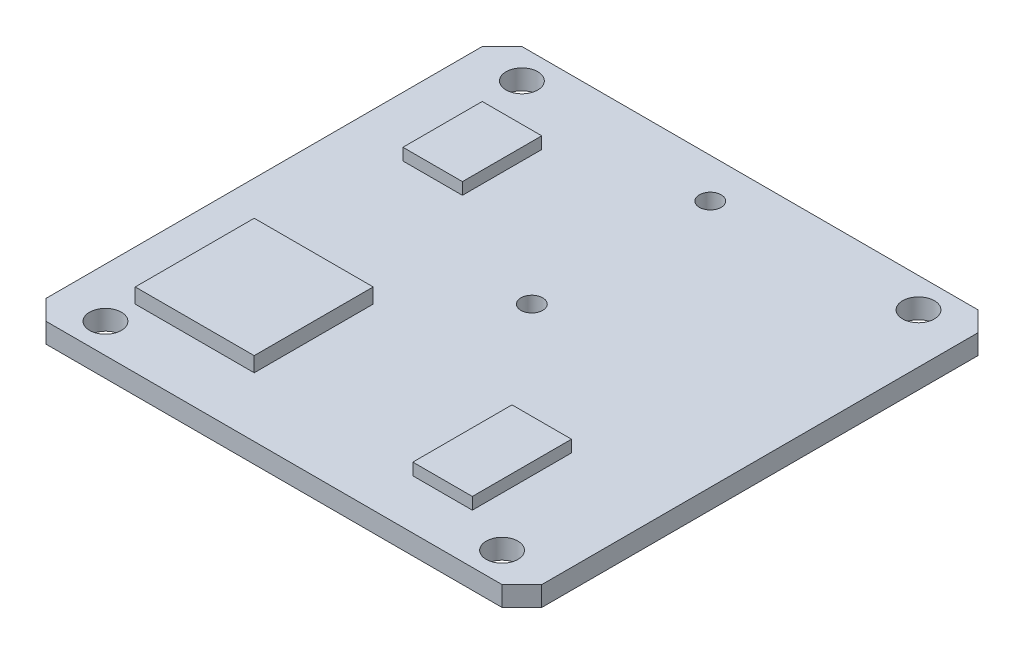
SolidWorks part; units mm, degrees
ref_plane "Front Plane" through (0, 0, 0) normal (0, 0, 1) x (1, 0, 0)
ref_plane "Top Plane" through (0, 0, 0) normal (0, 1, 0) x (1, 0, 0)
ref_plane "Right Plane" through (0, 0, 0) normal (1, 0, 0) x (0, 0, -1)
sketch "Sketch2" plane through (0, 0, 0) normal (0, 1, 0) x (1, 0, 0)
  line L1 (-25, 24) -> (25, 24)
  line L2 (-25, 24) -> (-25, -24)
  line L3 (-25, -24) -> (25, -24)
  line L4 (25, 24) -> (25, -24)
  point P4 (0, 24)
  point P6 (25, 0)
  dimension "D1" = 50
  dimension "D2" = 48
extrude "Boss-Extrude1" add sketch "Sketch2" along normal mid plane 2
chamfer "Chamfer1" distance 2 angle 45 4 edges at (-25, 0, -24) (-25, 0, 24) (25, 0, -24) (25, 0, 24)
sketch "Sketch3" plane through (0, 1, 0) normal (0, 1, 0) x (1, 0, 0)
  line L0 (0, -1.1) -> (0, 1.1) construction
  line L1 (-1.1, 0) -> (1.1, 0) construction
  circle A0 centre (-20, 21) radius 1.6
  circle A1 centre (20, 21) radius 1.6
  circle A2 centre (20, -21) radius 1.6
  circle A3 centre (-20, -21) radius 1.6
  circle A4 centre (0, 20) radius 1.1
  circle A5 centre (0, 2) radius 1.1
  point P2 (0, 0)
  dimension "D1" = 3.2
  dimension "D4" = 2.2
  dimension "D2" = 21
  dimension "D3" = 20
  dimension "D5" = 20
  dimension "D7" = 2
extrude "Cut-Extrude1" cut sketch "Sketch3" against normal through all
sketch "Sketch5" plane through (0, 1, 0) normal (0, 1, 0) x (1, 0, 0)
  line L1 (-8, -6) -> (-20, -6)
  line L2 (-8, -6) -> (-8, -18)
  line L3 (-8, -18) -> (-20, -18)
  line L4 (-20, -6) -> (-20, -18)
  line L5 (-8, -6) -> (-20, -18) construction
  line L6 (-8, -18) -> (-20, -6) construction
  point P0 (-14, -12)
  dimension "D1" = 12
  dimension "D2" = 12
  dimension "D3" = 12
  dimension "D4" = 14
extrude "Boss-Extrude2" add sketch "Sketch5" along normal blind 1.5
sketch "Sketch6" plane through (0, 1, 0) normal (0, 1, 0) x (1, 0, 0)
  line L5 (-13, 16) -> (-19, 16)
  line L6 (-13, 16) -> (-13, 8)
  line L11 (-13, 8) -> (-19, 8)
  line L12 (-19, 16) -> (-19, 8)
  line L13 (15, -9) -> (9, -9)
  line L14 (15, -9) -> (15, -19)
  line L15 (15, -19) -> (9, -19)
  line L16 (9, -9) -> (9, -19)
  point P8 (-13, 12)
  point P9 (-16, 8)
  point P10 (9, -14)
  point P11 (12, -9)
  dimension "D1" = 8
  dimension "D2" = 6
  dimension "D3" = 10
  dimension "D4" = 6
  dimension "D5" = 12
  dimension "D6" = 16
  dimension "D7" = 14
  dimension "D8" = 12
extrude "Boss-Extrude3" add sketch "Sketch6" along normal blind 1.2
